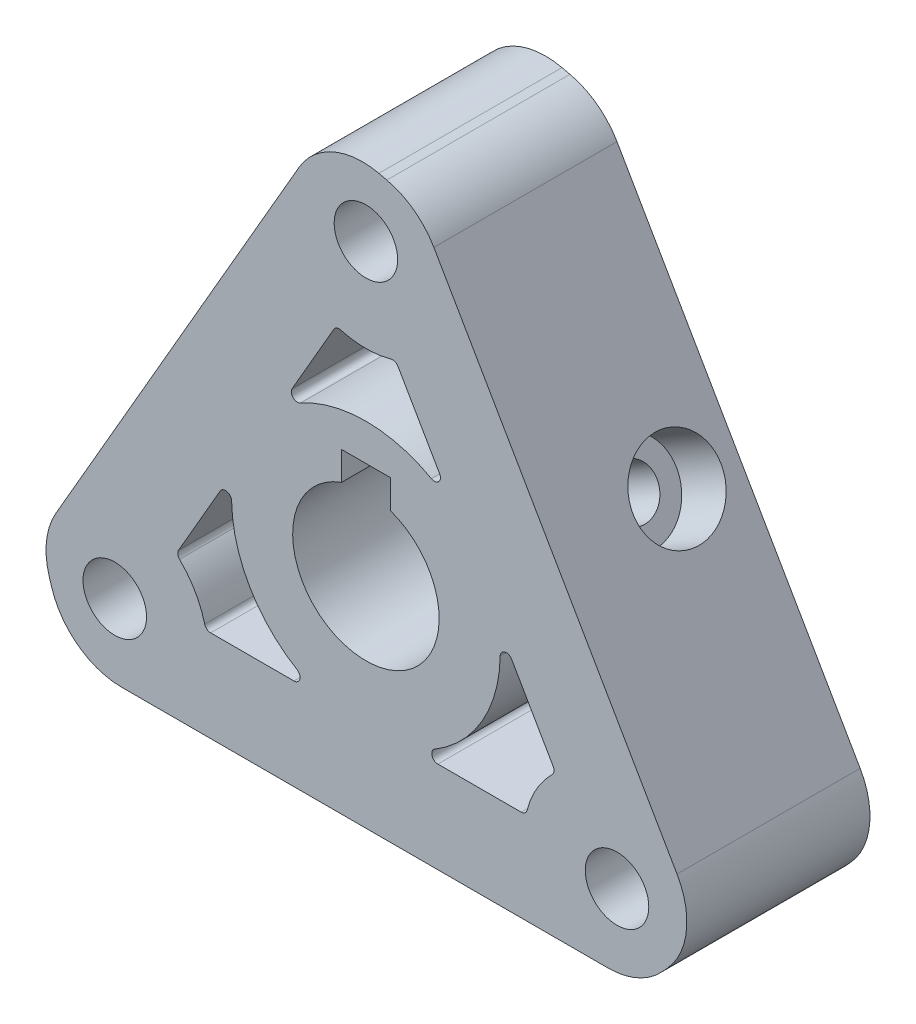
SolidWorks part; units mm, degrees
ref_plane "正面" through (0, 0, 0) normal (0, 0, 1) x (1, 0, 0)
ref_plane "平面" through (0, 0, 0) normal (0, 1, 0) x (1, 0, 0)
ref_plane "右側面" through (0, 0, 0) normal (1, 0, 0) x (0, 0, -1)
sketch "ｽｹｯﾁ1" plane through (0, 0, 0) normal (0, 0, 1) x (1, 0, 0)
  line L0 (0, 0) -> (-20.5681, -11.875) construction
  line L1 (0, 23.75) -> (-20.5681, -11.875) construction
  line L2 (-20.5681, -11.875) -> (20.5681, -11.875) construction
  line L3 (20.5681, -11.875) -> (0, 23.75) construction
  line L4 (-5.4793, 26.2596) -> (-25.3945, -8.2346)
  line L5 (-20.0019, -17.875) -> (19.8287, -17.875)
  line L6 (25.4811, -8.3846) -> (5.5659, 26.1096)
  line L7 (0, 35.75) -> (-30.9604, -17.875) construction
  line L8 (30.9604, -17.875) -> (0, 35.75) construction
  line L9 (1.7133, 28.9573) -> (1.0604, 29.1073)
  line L10 (-30.9604, -17.875) -> (30.9604, -17.875) construction
  line L11 (-25.9344, -12.9949) -> (-25.7378, -13.6352)
  line L12 (24.2211, -15.9624) -> (24.6774, -15.472)
  line L14 (-2, 4) -> (2, 4)
  line L15 (-2, 4) -> (-2, 8)
  line L16 (-2, 8) -> (2, 8)
  line L17 (2, 4) -> (2, 8)
  line L18 (-2, 4) -> (2, 8) construction
  line L19 (-2, 8) -> (2, 4) construction
  circle A0 centre (0, 0) radius 11.875 construction
  circle A1 centre (0, 23.75) radius 2.6
  circle A2 centre (20.5681, -11.875) radius 2.6
  circle A3 centre (-20.5681, -11.875) radius 2.6
  circle A4 centre (0, 0) radius 6
  arc A5 (-25.9344, -12.9949) -> (-25.3945, -8.2346) centre (-20.1984, -11.2346) cw
  arc A6 (-25.7378, -13.6352) -> (-20.0019, -17.875) centre (-20.0019, -11.875) ccw
  arc A7 (24.2211, -15.9624) -> (19.8287, -17.875) centre (19.8287, -11.875) cw
  arc A8 (24.6774, -15.472) -> (25.4811, -8.3846) centre (20.285, -11.3846) ccw
  arc A9 (1.7133, 28.9573) -> (5.5659, 26.1096) centre (0.3697, 23.1096) cw
  arc A10 (1.0604, 29.1073) -> (-5.4793, 26.2596) centre (-0.2831, 23.2596) ccw
  point P31 (0, 6)
  dimension "D1" = 5.2
  dimension "D2" = 5.2
  dimension "D3" = 5.2
  dimension "D5" = 12
  dimension "D7" = 6
  dimension "D4" = 23.75
  dimension "D8" = 4
  dimension "D9" = 4
  dimension "D6" = 6
extrude "ﾎﾞｽ - 押し出し1" add sketch "ｽｹｯﾁ1" along normal blind 15 contours L9 A10 L4 A5 L11 A6 L5 A7 L12 A8 L6 A9 A1 A2 A3 A4 L15 L16 L17
sketch "ｽｹｯﾁ3" plane through (0, -17.875, 0) normal (0, -1, 0) x (1, 0, 0)
  line L0 (-20.0019, 0) -> (19.8287, 0) construction
  circle A0 centre (0, 5) radius 2
  dimension "D1" = 5
  dimension "D2" = 4
extrude "ｶｯﾄ - 押し出し1" cut sketch "ｽｹｯﾁ3" against normal up to next
sketch "ｽｹｯﾁ4" plane through (0, -17.875, 0) normal (0, -1, 0) x (1, 0, 0)
  circle A0 centre (0, 5) radius 3.6
  dimension "D1" = 7.2
extrude "ｶｯﾄ - 押し出し2" cut sketch "ｽｹｯﾁ4" against normal blind 4.2
sketch "ｽｹｯﾁ6" plane through (0, 0, 0) normal (0, 0, -1) x (-1, 0, 0)
  circle A0 centre (0, 23.75) radius 5.1
  circle A1 centre (-20.5681, -11.875) radius 5.1
  circle A2 centre (20.5681, -11.875) radius 5.1
  dimension "D1" = 10.2
  dimension "D2" = 10.2
  dimension "D3" = 10.2
extrude "ｶｯﾄ - 押し出し4" cut sketch "ｽｹｯﾁ6" against normal blind 6.2
sketch "ｽｹｯﾁ7" plane through (15.4802, 8.9375, 0) normal (0.866, 0.5, 0) x (0, 0, -1)
  line L0 (0, -20.0019) -> (0, 19.8287) construction
  circle A0 centre (-5, 0) radius 2
  dimension "D1" = 5
  dimension "D2" = 4
extrude "ｶｯﾄ - 押し出し5" cut sketch "ｽｹｯﾁ7" against normal up to next
sketch "ｽｹｯﾁ8" plane through (15.4802, 8.9375, 0) normal (0.866, 0.5, 0) x (0, 0, -1)
  circle A0 centre (-5, 0) radius 3.6
  dimension "D1" = 7.2
extrude "ｶｯﾄ - 押し出し6" cut sketch "ｽｹｯﾁ8" against normal blind 4.2
sketch "ｽｹｯﾁ9" plane through (0, 0, 0) normal (0, 0, -1) x (-1, 0, 0)
  line L22 (0, 20.75) -> (-17.97, -10.375)
  line L23 (-17.97, -10.375) -> (17.97, -10.375)
  line L24 (17.97, -10.375) -> (0, 20.75)
  line L25 (0, 20.75) -> (-17.97, -10.375)
  line L26 (-17.97, -10.375) -> (17.97, -10.375)
  line L27 (17.97, -10.375) -> (0, 20.75)
  circle A9 centre (0, 0) radius 11
  arc A10 (-2, 5.6569) -> (2, 5.6569) centre (0, 0) ccw construction
  circle A11 centre (-20.5681, -11.875) radius 7.6
  circle A12 centre (-20.5681, -11.875) radius 5.1 construction
  circle A13 centre (0, 23.75) radius 7.6
  circle A14 centre (0, 23.75) radius 5.1 construction
  circle A15 centre (20.5681, -11.875) radius 7.6
  circle A16 centre (20.5681, -11.875) radius 5.1 construction
  circle M4 centre (-20.5681, -11.875) radius 5.1
  circle M5 centre (20.5681, -11.875) radius 5.1
  circle M6 centre (0, 23.75) radius 5.1
  dimension "D2" = 5
  dimension "D3" = 2.5
  dimension "D4" = 2.5
  dimension "D5" = 2.5
  dimension "D1" = 7.5
extrude "ｶｯﾄ - 押し出し7" cut sketch "ｽｹｯﾁ9" against normal through all contours A9 L25 L26 M4 | A9 L27 L25 M6 | A9 L26 L27 M5
fillet "ﾌｨﾚｯﾄ1" radius 0.5 12 edges at (2.4262, 16.5477, 7.5) (-2.4262, 16.5477, 7.5) (-7.1575, 8.3529, 7.5) (-10.8125, 2.0221, 7.5) (10.8125, 2.0221, 7.5) (7.1575, 8.3529, 7.5) (15.5438, -6.1727, 7.5) (13.1176, -10.375, 7.5) (3.655, -10.375, 7.5) (-3.655, -10.375, 7.5) (-15.5438, -6.1727, 7.5) (-13.1176, -10.375, 7.5)
